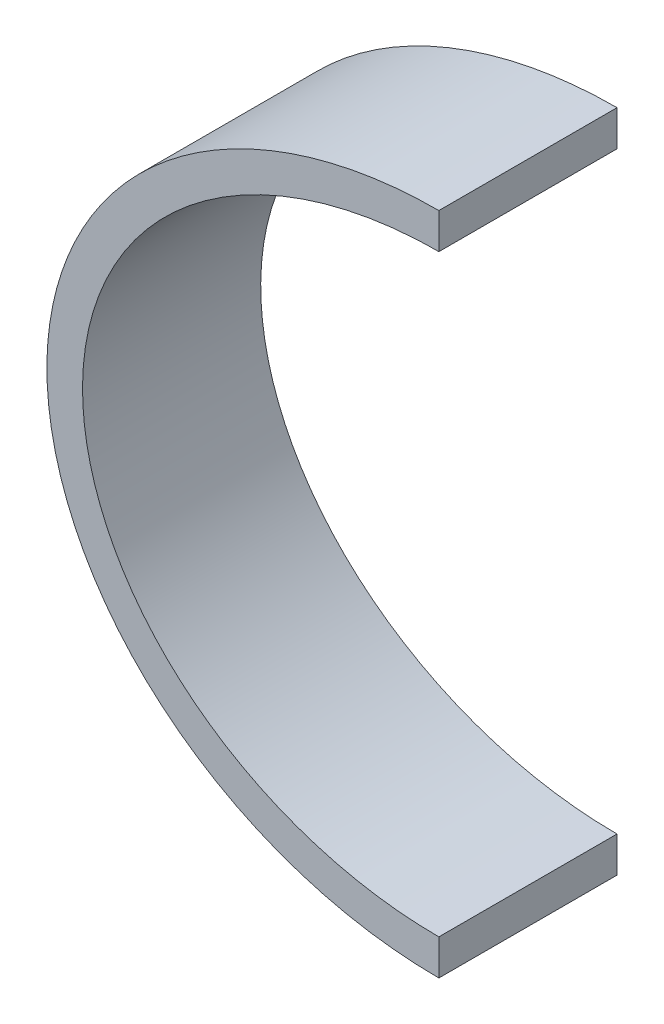
SolidWorks part; units mm, degrees
ref_plane "Front Plane" through (0, 0, 0) normal (0, 0, 1) x (1, 0, 0)
ref_plane "Top Plane" through (0, 0, 0) normal (0, 1, 0) x (1, 0, 0)
ref_plane "Right Plane" through (0, 0, 0) normal (1, 0, 0) x (0, 0, -1)
sketch "Sketch1" plane through (0, 0, 0) normal (0, 0, 1) x (1, 0, 0)
  line L0 (0, 9.3261) -> (0, 8.3261)
  line L1 (0, -8.3261) -> (0, -9.3261)
  ellipse E0 centre (0, 0) end of major axis (-11, 0) minor radius 9.3261 (0, 9.3261) -> (0, -9.3261) ccw
  ellipse E1 centre (0, 0) end of major axis (-10, 0) minor radius 8.3261 (0, 8.3261) -> (0, -8.3261) ccw
  dimension "D1" = 20
  dimension "D2" = 1
  dimension "D3" = 1
extrude "Boss-Extrude1" add sketch "Sketch1" along normal blind 5
